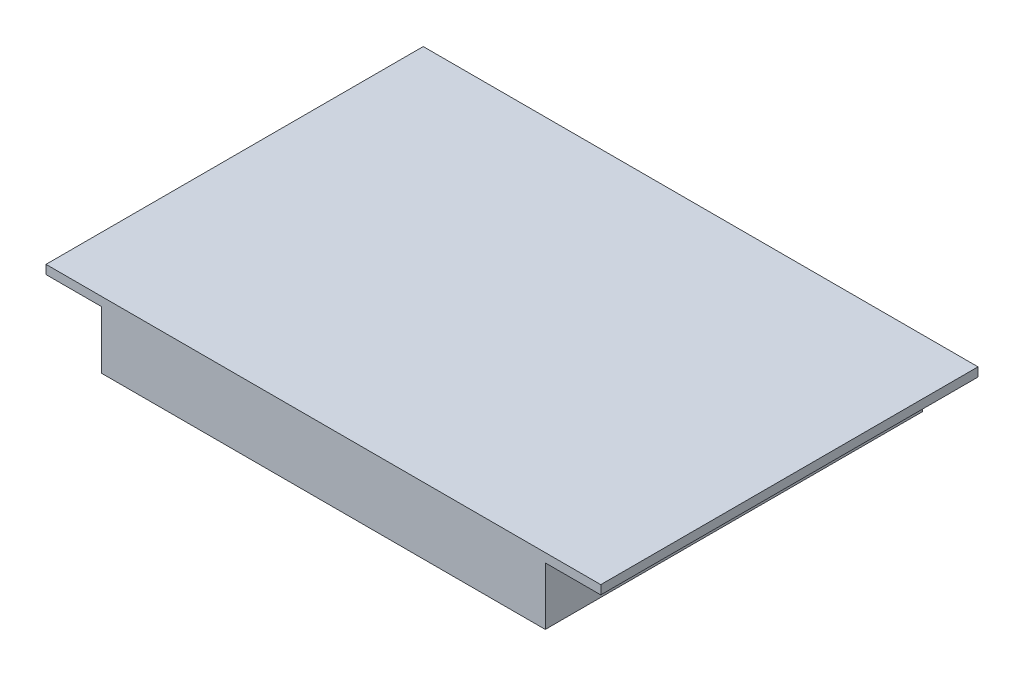
SolidWorks part; units mm, degrees
ref_plane "Front Plane" through (0, 0, 0) normal (0, 0, 1) x (1, 0, 0)
ref_plane "Top Plane" through (0, 0, 0) normal (0, 1, 0) x (1, 0, 0)
ref_plane "Right Plane" through (0, 0, 0) normal (1, 0, 0) x (0, 0, -1)
sketch "Sketch1" plane through (0, 0, 0) normal (0, 0, 1) x (1, 0, 0)
  line L0 (0, 0) -> (0, 15) construction
  line L1 (-100, -15) -> (100, -15)
  line L2 (-100, -15) -> (-100, 15)
  line L3 (-100, 15) -> (100, 15)
  line L4 (100, -15) -> (100, 15)
  line L5 (-100, -15) -> (100, 15) construction
  line L6 (-100, 15) -> (100, -15) construction
  line L7 (-100, 15) -> (-125, 15)
  line L8 (-100, 15) -> (-100, 11)
  line L9 (-100, 11) -> (-125, 11)
  line L10 (-125, 15) -> (-125, 11)
  line L11 (100, 15) -> (125, 15)
  line L12 (125, 15) -> (125, 11)
  line L13 (100, 11) -> (125, 11)
  point P0 (0, 0)
  dimension "D1" = 200
  dimension "D2" = 30
  dimension "D3" = 25
  dimension "D4" = 4
extrude "Boss-Extrude1" add sketch "Sketch1" along normal mid plane 170 contours L1 L4 L3 L2 | L7 L10 L9 L2 | L4 L13 L12 L11
